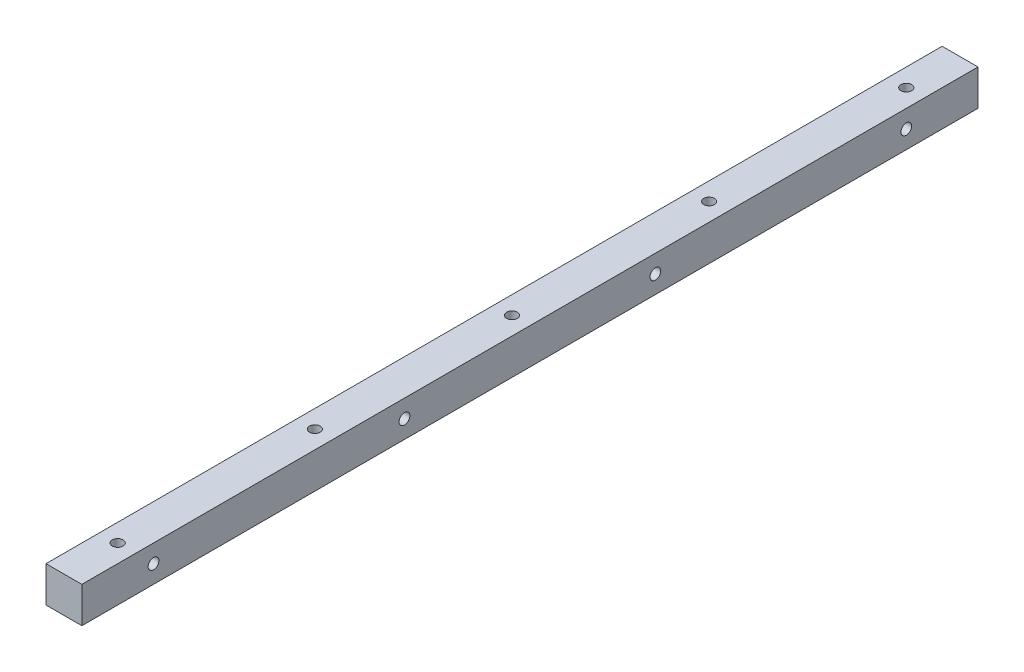
SolidWorks part; units mm, degrees
ref_plane "Front Plane" through (0, 0, 0) normal (0, 0, 1) x (1, 0, 0)
ref_plane "Top Plane" through (0, 0, 0) normal (0, 1, 0) x (1, 0, 0)
ref_plane "Right Plane" through (0, 0, 0) normal (1, 0, 0) x (0, 0, -1)
sketch "Sketch1" plane through (0, 0, 0) normal (0, 0, 1) x (1, 0, 0)
  line L1 (0, 0) -> (10, 0)
  line L2 (0, 0) -> (0, 10)
  line L3 (0, 10) -> (10, 10)
  line L4 (10, 0) -> (10, 10)
  dimension "D1" = 10
  dimension "D2" = 10
extrude "Extrude1" add sketch "Sketch1" along normal blind 250
sketch "Sketch4" plane through (0, 10, 0) normal (0, 1, 0) x (-1, 0, 0)
  line L1 (0, 5.5) -> (0, -5.5) construction
  circle A0 centre (-5, 15) radius 1.5
  dimension "D1" = 3
  dimension "D2" = 5
  dimension "D3" = 15
extrude "Cut-Extrude3" cut sketch "Sketch4" against normal through all
pattern_linear "LPattern2" count 5 spacing 55 along (0, 0, 1) of "Cut-Extrude3"
sketch "Sketch5" plane through (0, 0, 0) normal (-1, 0, 0) x (0, 0, 1)
  line L0 (250, 10) -> (250, 0) construction
  circle A0 centre (20, 5) radius 1.5
  circle A1 centre (90, 5) radius 1.5
  circle A2 centre (230, 5) radius 1.5
  circle A3 centre (160, 5) radius 1.5
  dimension "D6" = 3
  dimension "D1" = 5
  dimension "D2" = 20
  dimension "D3" = 20
  dimension "D4" = 70
  dimension "D5" = 70
  dimension "D7" = 70
extrude "Cut-Extrude4" cut sketch "Sketch5" against normal through all
